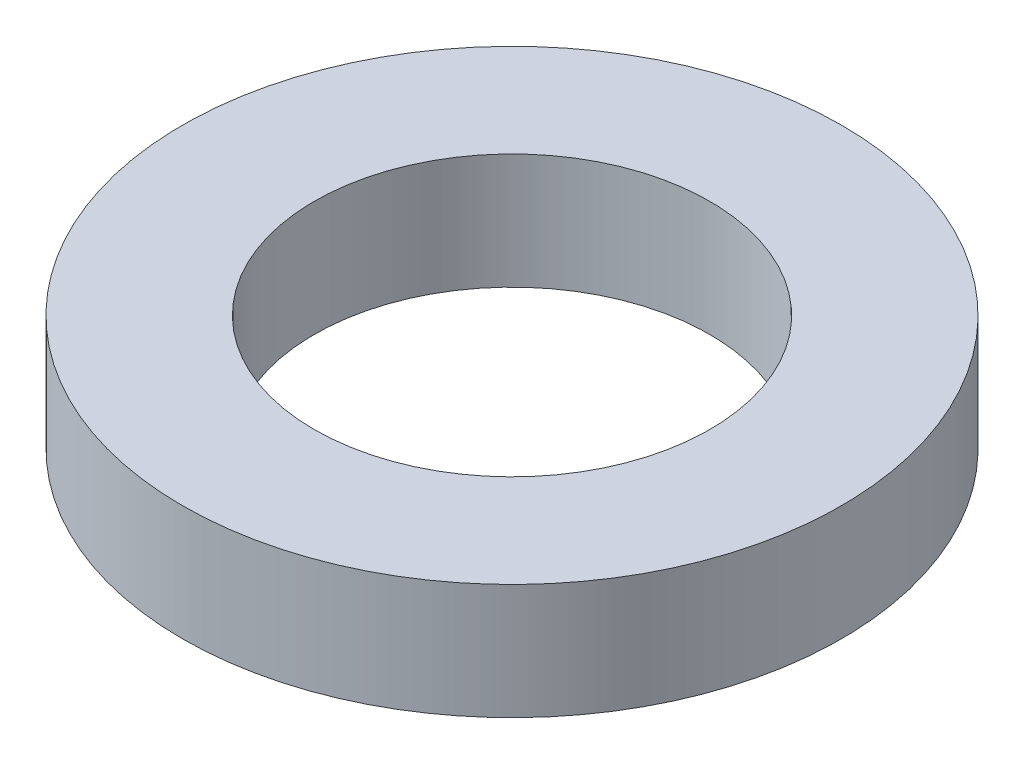
SolidWorks part; units mm, degrees
ref_plane "Front Plane" through (0, 0, 0) normal (0, 0, 1) x (1, 0, 0)
ref_plane "Top Plane" through (0, 0, 0) normal (0, 1, 0) x (1, 0, 0)
ref_plane "Right Plane" through (0, 0, 0) normal (1, 0, 0) x (0, 0, -1)
sketch "Sketch1" plane through (0, 0, 0) normal (0, 1, 0) x (1, 0, 0)
  circle A0 centre (0, 0) radius 6
  circle A1 centre (0, 0) radius 10
  dimension "D1" = 12
  dimension "D2" = 4
extrude "Boss-Extrude1" add sketch "Sketch1" along normal blind 3.5
